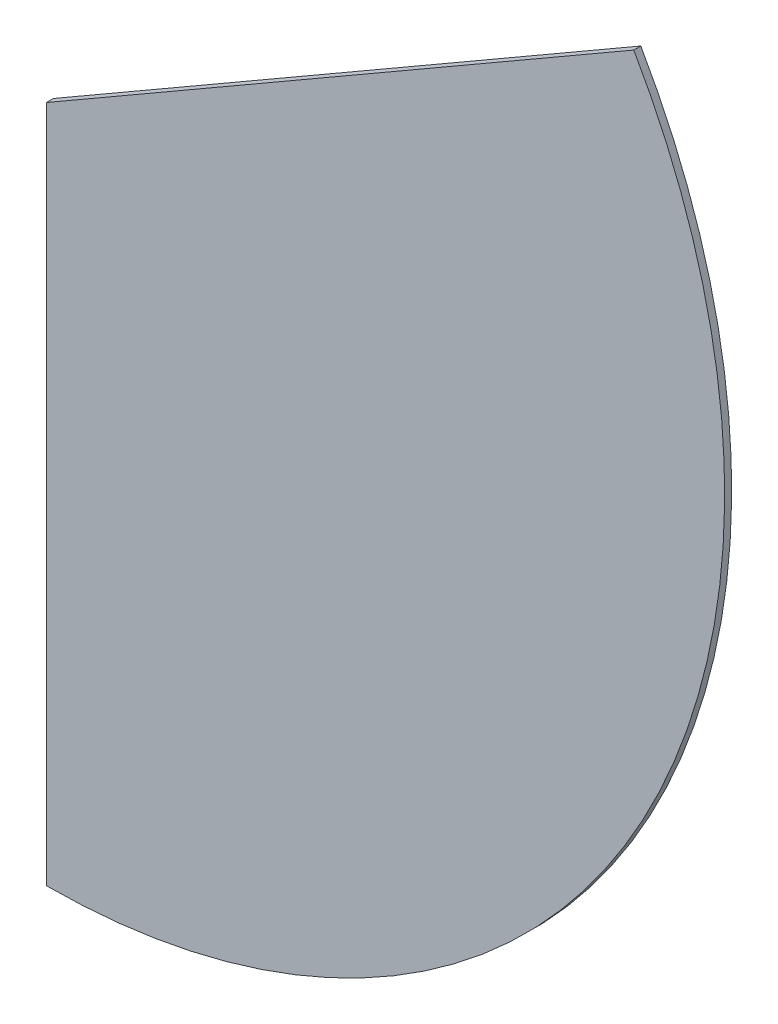
SolidWorks part; units mm, degrees
ref_plane "前基準面" through (0, 0, 0) normal (0, 0, 1) x (1, 0, 0)
ref_plane "上基準面" through (0, 0, 0) normal (0, 1, 0) x (1, 0, 0)
ref_plane "右基準面" through (0, 0, 0) normal (1, 0, 0) x (0, 0, -1)
sketch "草圖1" plane through (0, 0, 0) normal (0, 0, 1) x (1, 0, 0)
  line L0 (0, 0) -> (0, -155)
  line L1 (0, 0) -> (134.2339, 77.5)
  arc A0 (134.2339, 77.5) -> (0, -155) centre (0, 0) cw
  dimension "D1" = 155
  dimension "D2" = 120
extrude "填料-伸長1" add sketch "草圖1" along normal blind 1.6
